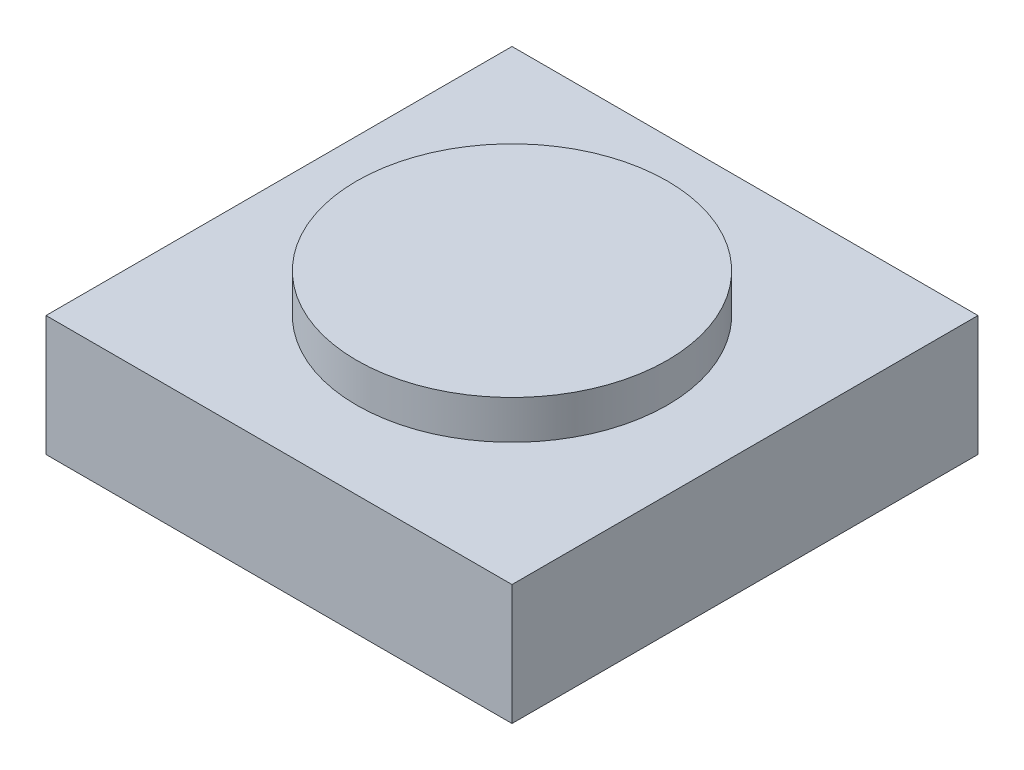
SolidWorks part; units mm, degrees
ref_plane "前视" through (0, 0, 0) normal (0, 0, 1) x (1, 0, 0)
ref_plane "上视" through (0, 0, 0) normal (0, 1, 0) x (1, 0, 0)
ref_plane "右视" through (0, 0, 0) normal (1, 0, 0) x (0, 0, -1)
sketch "草图1" plane through (0, 0, 0) normal (0, 1, 0) x (1, 0, 0)
  line L0 (0, 96.9306) -> (0, -101.3275) construction
  line L1 (-119.7143, 0) -> (134.9034, 0) construction
  line L3 (-6, 6) -> (6, 6)
  line L4 (-6, 6) -> (-6, -6)
  line L5 (-6, -6) -> (6, -6)
  line L6 (6, 6) -> (6, -6)
  dimension "D1" = 12
  dimension "D2" = 12
extrude "拉伸1" add sketch "草图1" along normal blind 3.1
sketch "草图2" plane through (0, 3.1, 0) normal (0, 1, 0) x (-1, 0, 0)
  line L0 (-6, 0) -> (8.7109, 0) construction
  line L1 (-6, 6) -> (-6, -6) construction
  line L2 (0, -7.8518) -> (0, 10.0992) construction
  circle A0 centre (0, 0) radius 4
  dimension "D1" = 8
extrude "拉伸2" add sketch "草图2" along normal blind 1
sketch "草图3" plane through (-6, 0, 0) normal (-1, 0, 0) x (0, 0, 1)
  line L0 (0, -6.9925) -> (0, 14.8526) construction
sketch "草图4" plane through (0, 4.1, 0) normal (0, 1, 0) x (-1, 0, 0)
  line L0 (0, -4.1469) -> (0, 4.9476) construction
  line L1 (-3.9082, 0) -> (5.1305, 0) construction
sketch "草图5" plane through (0, 0, 0) normal (0, -1, 0) x (1, 0, 0)
  line L0 (10.1949, 0) -> (-13.2034, 0) construction
  line L1 (0, 8.665) -> (0, -9.2576) construction
